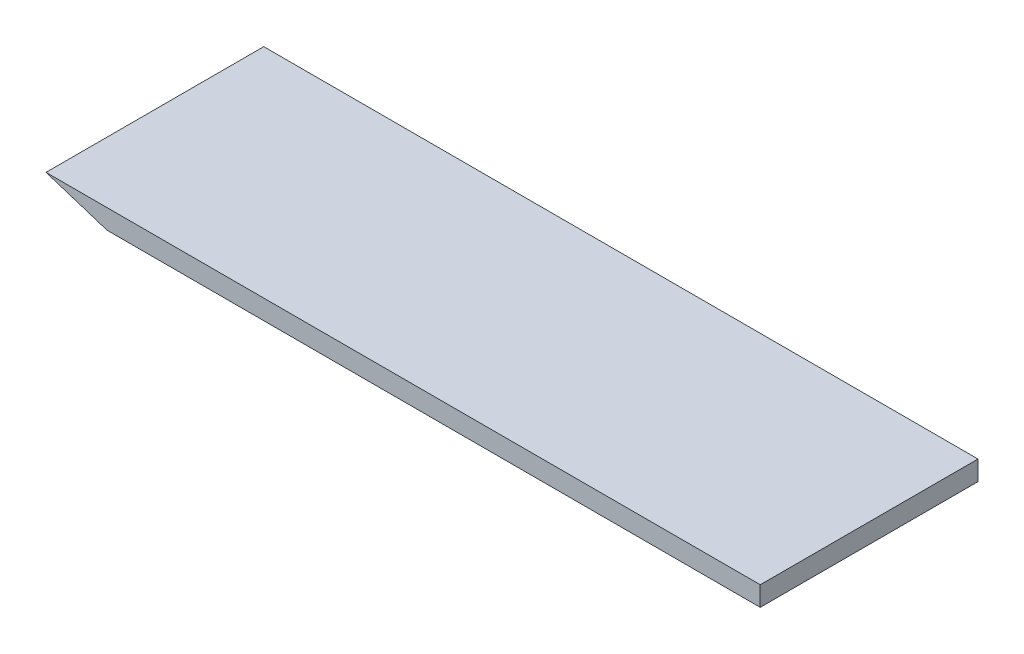
SolidWorks part; units mm, degrees
ref_plane "Front Plane" through (0, 0, 0) normal (0, 0, 1) x (1, 0, 0)
ref_plane "Top Plane" through (0, 0, 0) normal (0, 1, 0) x (1, 0, 0)
ref_plane "Right Plane" through (0, 0, 0) normal (1, 0, 0) x (0, 0, -1)
sketch "Sketch1" plane through (0, 0, 0) normal (0, 0, 1) x (1, 0, 0)
  line L0 (0, 0) -> (328, 0)
  line L1 (328, 0) -> (328, -9)
  line L2 (328, -9) -> (28, -9)
  line L3 (28, -9) -> (0, 0)
  dimension "D1" = 9
  dimension "D2" = 300
  dimension "D3" = 28
extrude "Boss-Extrude1" add sketch "Sketch1" along normal blind 100 contours L3 L0 L1 L2
